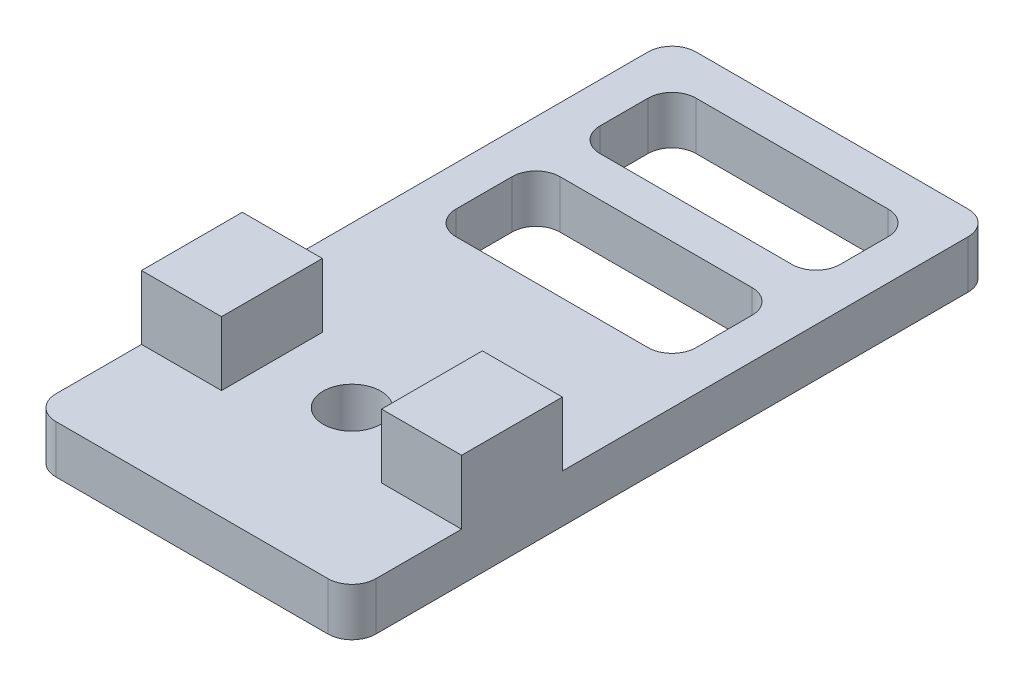
SolidWorks part; units mm, degrees
ref_plane "Front Plane" through (0, 0, 0) normal (0, 0, 1) x (1, 0, 0)
ref_plane "Top Plane" through (0, 0, 0) normal (0, 1, 0) x (1, 0, 0)
ref_plane "Right Plane" through (0, 0, 0) normal (1, 0, 0) x (0, 0, -1)
sketch "Sketch1" plane through (0, 0, 0) normal (0, 1, 0) x (1, 0, 0)
  line L0 (10, 37.5) -> (10, 22.5) construction
  line L1 (0, 0) -> (20, 0)
  line L2 (0, 0) -> (0, 40)
  line L3 (0, 40) -> (20, 40)
  line L4 (20, 0) -> (20, 40)
  line L5 (2.5, 37.5) -> (17.5, 37.5)
  line L6 (2.5, 37.5) -> (2.5, 22.5)
  line L7 (2.5, 22.5) -> (17.5, 22.5)
  line L8 (17.5, 37.5) -> (17.5, 22.5)
  line L9 (10, 40) -> (10, 0) construction
  line L11 (2.5, 31.5) -> (17.5, 31.5)
  line L12 (2.5, 31.5) -> (2.5, 29)
  line L13 (2.5, 29) -> (17.5, 29)
  line L14 (17.5, 31.5) -> (17.5, 29)
  line L15 (0, 0) -> (20, 0) construction
  line L16 (0, 0) -> (0, 20) construction
  line L17 (0, 20) -> (20, 20) construction
  line L18 (20, 0) -> (20, 20) construction
  dimension "D1" = 20
  dimension "D2" = 40
  dimension "D3" = 15
  dimension "D4" = 2.5
  dimension "D5" = 15
  dimension "D6" = 2.5
  dimension "D7" = 6
  dimension "D8" = 20
extrude "Boss-Extrude1" add sketch "Sketch1" along normal blind 3 contours L1 L4 L3 L2 L5 L8 L7 L6 | L12 L11 L14 L13
sketch "Sketch2" plane through (0, 3, 0) normal (0, 1, 0) x (1, 0, 0)
  line L0 (20, 0) -> (20, 40) construction
  line L1 (0, 0) -> (20, 0) construction
  line L2 (0, 0) -> (0, 20) construction
  line L3 (0, 20) -> (20, 20) construction
  line L4 (20, 0) -> (20, 20) construction
  line L5 (0, 10) -> (20, 10) construction
  line L7 (0, 13.15) -> (20, 13.15)
  line L8 (0, 13.15) -> (0, 6.85)
  line L9 (0, 6.85) -> (20, 6.85)
  line L10 (20, 13.15) -> (20, 6.85)
  line L11 (0, 13.15) -> (20, 6.85) construction
  line L12 (0, 6.85) -> (20, 13.15) construction
  line L13 (5, 13.15) -> (15, 13.15)
  line L14 (5, 13.15) -> (5, 6.85)
  line L15 (5, 6.85) -> (15, 6.85)
  line L16 (15, 13.15) -> (15, 6.85)
  line L17 (5, 13.15) -> (15, 6.85) construction
  line L18 (5, 6.85) -> (15, 13.15) construction
  point P9 (10, 10)
  point P15 (10, 10)
  line M9 (20, 0) -> (20, 40)
  line M11 (0, 40) -> (0, 0)
  dimension "D1" = 20
  dimension "D2" = 6.3
  dimension "D3" = 10
extrude "Boss-Extrude2" add sketch "Sketch2" along normal blind 4 contours L14 L7 L9 M11 | L7 L16 L9 M9
sketch "Sketch3" plane through (0, 3, 0) normal (0, 1, 0) x (1, 0, 0)
  line L0 (5, 10) -> (15, 10) construction
  line L1 (5, 13.15) -> (5, 6.85) construction
  line L2 (15, 13.15) -> (15, 6.85) construction
  point P6 (10, 10)
hole_wizard "M3 Clearance Hole1" positions "Sketch3" profile "Sketch4" hole size "M3" standard "ANSI Metric"
sketch "Sketch4" plane through (10, 3, -10) normal (1, 0, 0) x (0, 0, 1)
  line L0 (0, 0) -> (0, 11.0815)
  line L1 (0, 11.0815) -> (1.8, 10)
  line L2 (1.8, 10) -> (1.8, 0)
  line L5 (1.8, 0) -> (0, 0)
  line L10 (0, 11.0815) -> (-1.8, 10) construction
  line L11 (0, -6.35) -> (0, 107.95) construction
  dimension "Hole Dia." = 3.6
  dimension "Hole Depth" = 10
  dimension "Drill Angle" = 118
fillet "Fillet1" radius 1.5 12 edges at (20, 1.5, 0) (0, 1.5, 0) (0, 1.5, -40) (20, 1.5, -40) (2.5, 1.5, -22.5) (2.5, 1.5, -29) (17.5, 1.5, -29) (17.5, 1.5, -22.5) (17.5, 1.5, -31.5) (2.5, 1.5, -31.5) (2.5, 1.5, -37.5) (17.5, 1.5, -37.5)
